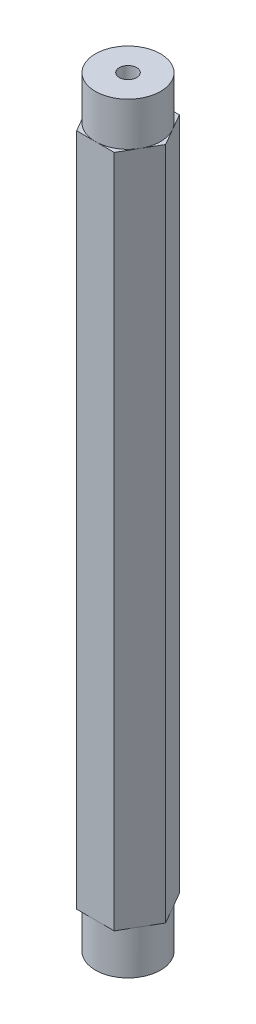
SolidWorks part; units mm, degrees
material "Alum Plate"
ref_plane "Front Plane" through (0, 0, 0) normal (0, 0, 1) x (1, 0, 0)
ref_plane "Top Plane" through (0, 0, 0) normal (0, 1, 0) x (1, 0, 0)
ref_plane "Right Plane" through (0, 0, 0) normal (1, 0, 0) x (0, 0, -1)
other "Bounding Box"
ref_plane "Default Plane" through (-8.9266, -12.7485, 0) normal (-0.1736, 0.9848, 0) x (0.9848, 0.1736, 0)
sketch "Sketch1" plane through (0, 0, 0) normal (0, 1, 0) x (1, 0, 0)
  line L1 (1.3748, -2.3812) -> (2.7496, 0)
  line L2 (2.7496, 0) -> (1.3748, 2.3813)
  line L3 (1.3748, 2.3813) -> (-1.3748, 2.3813)
  line L4 (-1.3748, 2.3813) -> (-2.7496, 0)
  line L5 (-2.7496, 0) -> (-1.3748, -2.3812)
  line L6 (-1.3748, -2.3812) -> (1.3748, -2.3812)
  circle A0 centre (0, 0) radius 2.3813 construction
  circle A1 centre (0, 0) radius 0.635
  dimension "D2" = 1.27
  dimension "D1" = 4.7625
extrude "Boss-Extrude1" add sketch "Sketch1" along normal mid plane 49.276
sketch "Sketch2" plane through (0, 24.638, 0) normal (0, 1, 0) x (1, 0, 0)
  circle A0 centre (0, 0) radius 2.3813
  circle A1 centre (0, 0) radius 0.635 construction
  circle A2 centre (0, 0) radius 0.635
  dimension "D1" = 4.7625
extrude "Boss-Extrude2" add sketch "Sketch2" along normal blind 3.175
sketch "Sketch3" plane through (0, -24.638, 0) normal (0, -1, 0) x (1, 0, 0)
  circle A0 centre (0, 0) radius 0.635 construction
  circle A1 centre (0, 0) radius 0.635
  circle A2 centre (0, 0) radius 2.3813
  dimension "D1" = 4.7625
extrude "Boss-Extrude3" add sketch "Sketch3" along normal blind 3.175
